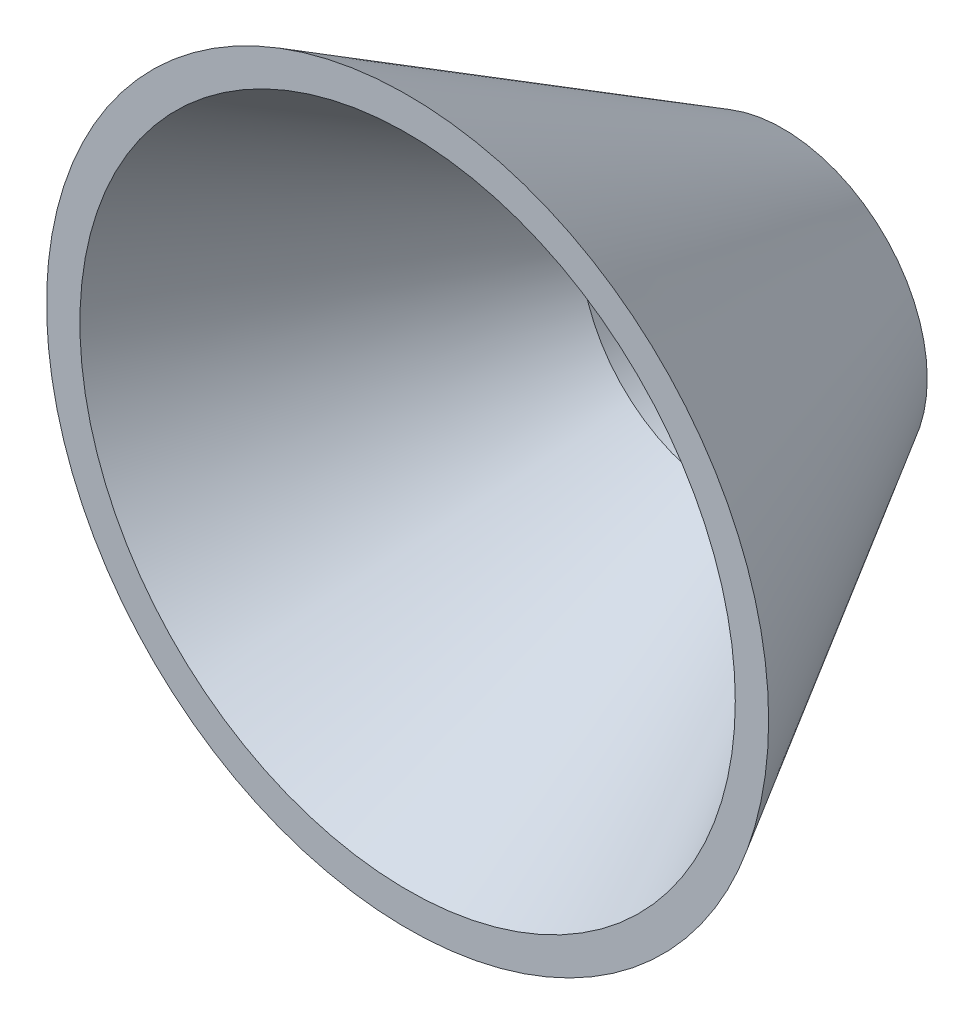
SolidWorks part; units mm, degrees
material "Silikongummi"
ref_plane "Ebene vorne" through (0, 0, 0) normal (0, 0, 1) x (1, 0, 0)
ref_plane "Ebene oben" through (0, 0, 0) normal (0, 1, 0) x (1, 0, 0)
ref_plane "Ebene rechts" through (0, 0, 0) normal (1, 0, 0) x (0, 0, -1)
sketch "Skizze2" plane through (0, 0, 0) normal (0, 0, 1) x (1, 0, 0)
  circle A0 centre (0, 0) radius 25
  dimension "D1" = 50
extrude "Aufsatz-Linear austragen1" add sketch "Skizze2" against normal blind 50 draft 30
shell "Wandung1" thickness 2
sketch "Skizze3" plane through (0, 0, 0) normal (0, 0, 1) x (1, 0, 0)
  circle A0 centre (0, 0) radius 10
  dimension "D1" = 20
extrude "Schnitt-Linear austragen1" cut sketch "Skizze3" against normal through all both and the other way through all
